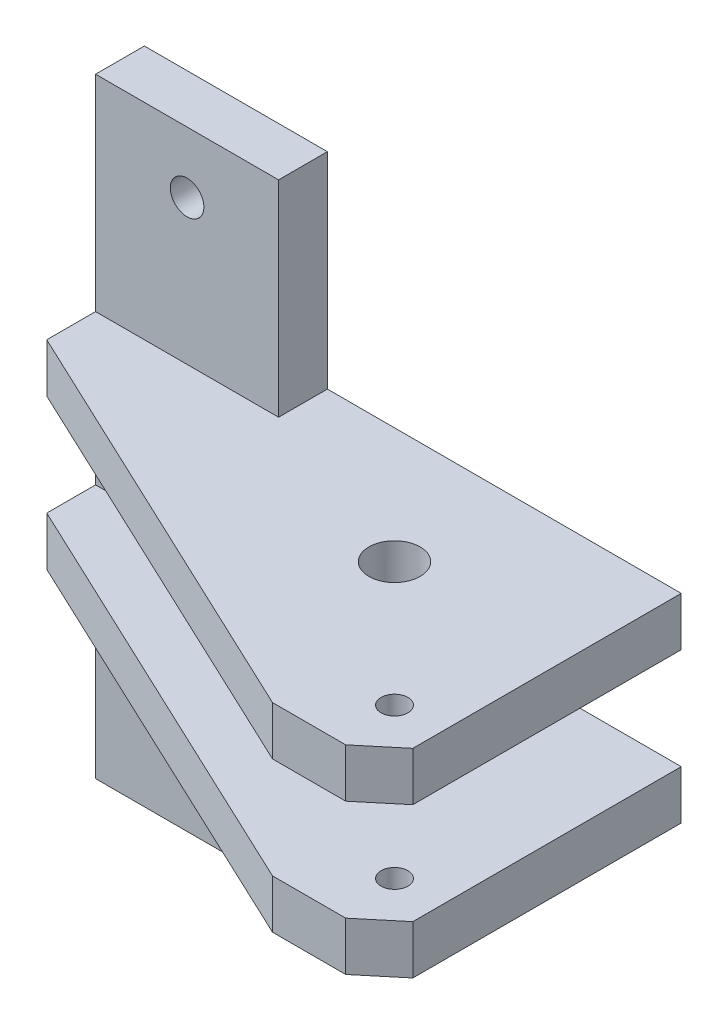
SolidWorks part; units mm, degrees
ref_plane "前视基准面" through (0, 0, 0) normal (0, 0, 1) x (1, 0, 0)
ref_plane "上视基准面" through (0, 0, 0) normal (0, 1, 0) x (1, 0, 0)
ref_plane "右视基准面" through (0, 0, 0) normal (1, 0, 0) x (0, 0, -1)
other "Configuration Table"
sketch "草图1" plane through (0, 0, 0) normal (0, 0, 1) x (1, 0, 0)
  line L1 (-30, -50) -> (0, -50)
  line L2 (-30, -50) -> (-30, 50)
  line L3 (-30, 50) -> (0, 50)
  line L4 (0, -50) -> (0, 50)
  circle A0 centre (-15, -40) radius 2.75
  circle A1 centre (-15, 40) radius 2.75
extrude "凸台-拉伸2" add sketch "草图1" along normal blind 8
sketch "草图3" plane through (0, 0, 0) normal (0, 1, 0) x (1, 0, 0)
  line L0 (-30, 0) -> (58, 0)
  line L1 (58, 0) -> (58, -44)
  line L2 (58, -44) -> (52, -49)
  line L3 (52, -49) -> (40, -49)
  line L4 (40, -49) -> (-30, -16)
  line L5 (-30, -16) -> (-30, 0)
extrude "凸台-拉伸4" add sketch "草图3" against normal mid plane 32.6
sketch "草图4" plane through (0, 0, 0) normal (0, 1, 0) x (1, 0, 0)
  line L0 (-30, -8) -> (0, -8)
  line L1 (0, -8) -> (0, 0)
  line L2 (0, 0) -> (58, 0)
  line L3 (58, 0) -> (58, -44)
  line L4 (58, -44) -> (52, -49)
  line L5 (52, -49) -> (40, -49)
  line L6 (40, -49) -> (-30, -16)
  line L7 (-30, -16) -> (-30, -8)
extrude "切除-拉伸1" cut sketch "草图4" against normal mid plane 16.6
sketch "草图5" plane through (0, 0, 0) normal (0, 1, 0) x (1, 0, 0)
  circle A0 centre (30, -19) radius 5.5
extrude "凸台-拉伸5" add sketch "草图5" against normal mid plane 16.6
sketch "草图6" plane through (0, 0, 0) normal (0, 1, 0) x (1, 0, 0)
  circle A0 centre (30, -19) radius 5.5
extrude "切除-拉伸2" cut sketch "草图6" against normal mid plane 15
sketch "草图7" plane through (0, 0, 0) normal (0, 1, 0) x (1, 0, 0)
  circle A0 centre (30, -19) radius 4.2
  circle A1 centre (50.3647, -39.3647) radius 2.2
extrude "切除-拉伸3" cut sketch "草图7" against normal mid plane 42.6
